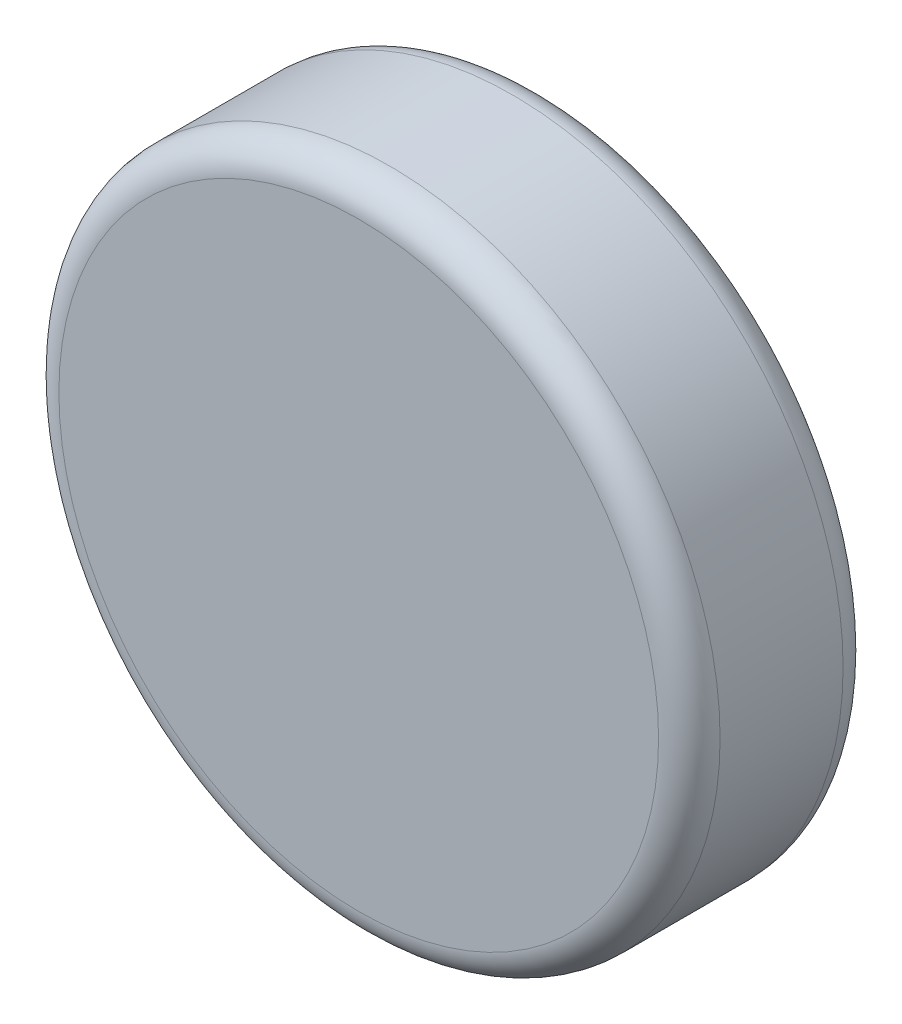
SolidWorks part; units mm, degrees
ref_plane "Plan de face" through (0, 0, 0) normal (0, 0, 1) x (1, 0, 0)
ref_plane "Plan de dessus" through (0, 0, 0) normal (0, 1, 0) x (1, 0, 0)
ref_plane "Plan de droite" through (0, 0, 0) normal (1, 0, 0) x (0, 0, -1)
sketch "Esquisse1" plane through (0, 0, 0) normal (0, 0, 1) x (1, 0, 0)
  circle A0 centre (0, 0) radius 10.75
  dimension "D1" = 21.5
extrude "Boss.-Extru.1" add sketch "Esquisse1" along normal blind 6
sketch "Esquisse3" plane through (0, 0, 0) normal (0, 0, -1) x (-1, 0, 0)
  line L0 (0, 0) -> (0, 4.0852) construction
  circle A0 centre (-2.5, 0) radius 0.7
  circle A1 centre (2.5, 0) radius 0.7
  dimension "D1" = 1.4
  dimension "D2" = 1.4
  dimension "D3" = 5
extrude "Boss.-Extru.2" add sketch "Esquisse3" along normal blind 3
fillet "Congé1" radius 1 2 edges at (10.75, 0, 6) (10.75, 0, 0)
